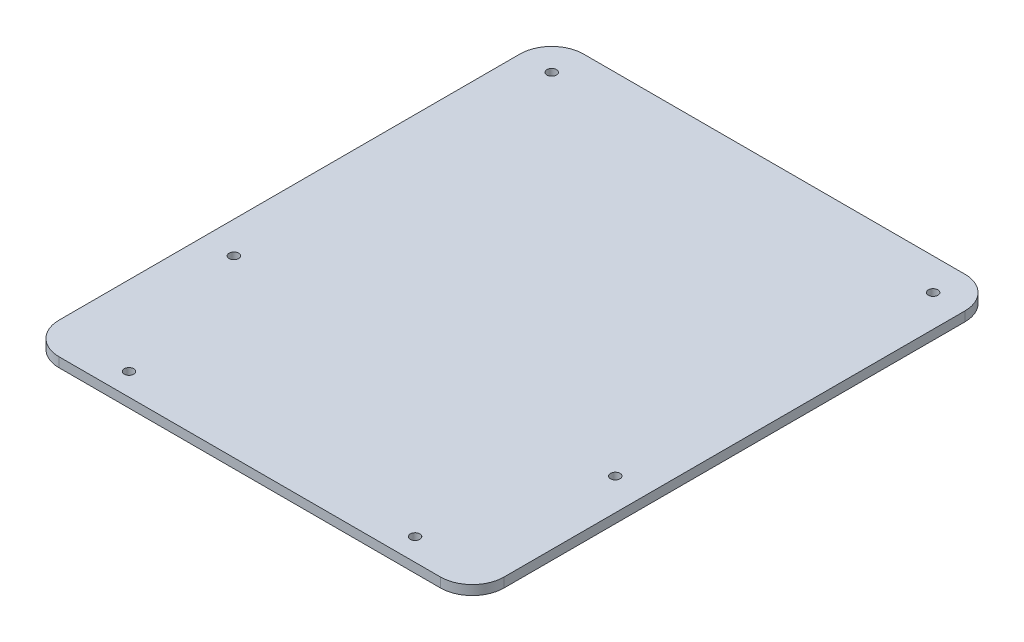
SolidWorks part; units mm, degrees
material "Thornel Mat VMA"
ref_plane "前视基准面" through (0, 0, 0) normal (0, 0, 1) x (1, 0, 0)
ref_plane "上视基准面" through (0, 0, 0) normal (0, 1, 0) x (1, 0, 0)
ref_plane "右视基准面" through (0, 0, 0) normal (1, 0, 0) x (0, 0, -1)
other "Configuration Table"
sketch "草图1" plane through (0, 0, 0) normal (0, 1, 0) x (1, 0, 0)
  line L0 (-70, 105) -> (-70, 50)
  line L1 (-140, -105) -> (140, -105)
  line L2 (-140, -105) -> (-140, 105)
  line L3 (-140, 105) -> (140, 105)
  line L4 (140, -105) -> (140, 105)
  line L5 (-140, -105) -> (140, 105) construction
  line L6 (-140, 105) -> (140, -105) construction
  line L7 (-70, 50) -> (-140, 50)
  line L8 (0, 0) -> (0, 133.0759) construction
  line L9 (0, 0) -> (180.8877, 0) construction
  line L10 (70, 50) -> (140, 50)
  line L11 (70, 105) -> (70, 50)
  line L12 (70, -50) -> (140, -50)
  line L13 (70, -105) -> (70, -50)
  line L14 (-70, -105) -> (-70, -50)
  line L15 (-70, -50) -> (-140, -50)
  line L16 (-70, 50) -> (-70, -50)
  line L17 (70, 50) -> (70, -50)
  point P0 (0, 0)
  dimension "D1" = 210
  dimension "D2" = 280
  dimension "D3" = 100
  dimension "D4" = 140
extrude "凸台-拉伸1" add sketch "草图1" along normal blind 3 contours L15 L14 L1 L13 L12 L4 L10 L11 L3 L0 L7 L2
sketch "草图2" plane through (0, 3, 0) normal (0, 1, 0) x (1, 0, 0)
  line L0 (-185.4975, 0) -> (185.4975, 0) construction
  line L1 (0, -169.2547) -> (0, 169.2547) construction
  circle A1 centre (-60, 50) radius 1.5
  circle A3 centre (60, 50) radius 1.5
  circle A8 centre (60, -50) radius 1.5
  circle A10 centre (-60, -50) radius 1.5
  circle A11 centre (-45, 98) radius 1.5
  circle A12 centre (45, 98) radius 1.5
  circle A13 centre (45, -98) radius 1.5
  circle A14 centre (-45, -98) radius 1.5
  point P6 (0, 0)
  point P10 (0, 0)
  dimension "D1" = 3
  dimension "D3" = 3
  dimension "D5" = 98
  dimension "D8" = 50
  dimension "D2" = 45
  dimension "D4" = 60
extrude "切除-拉伸1" cut sketch "草图2" against normal blind 3
fillet "圆角1" radius 10 2 edges at (70, 1.5, 105) (-70, 1.5, 105)
sketch "草图3" plane through (0, 3, 0) normal (0, 1, 0) x (1, 0, 0)
  line L0 (-70, 60) -> (-70, 105)
  line L1 (-70, 105) -> (-70, -95) construction
  line L2 (-70, 60) -> (70, 60)
  line L3 (70, 105) -> (70, -95) construction
  line L4 (70, 60) -> (70, 105)
  line L5 (70, 105) -> (-70, 105)
  line L6 (0, 0) -> (103.1615, 0) construction
  dimension "D1" = 45
  dimension "D2" = 60
extrude "切除-拉伸2" cut sketch "草图3" against normal blind 10
fillet "圆角2" radius 10 2 edges at (70, 1.5, -60) (-70, 1.5, -60)
